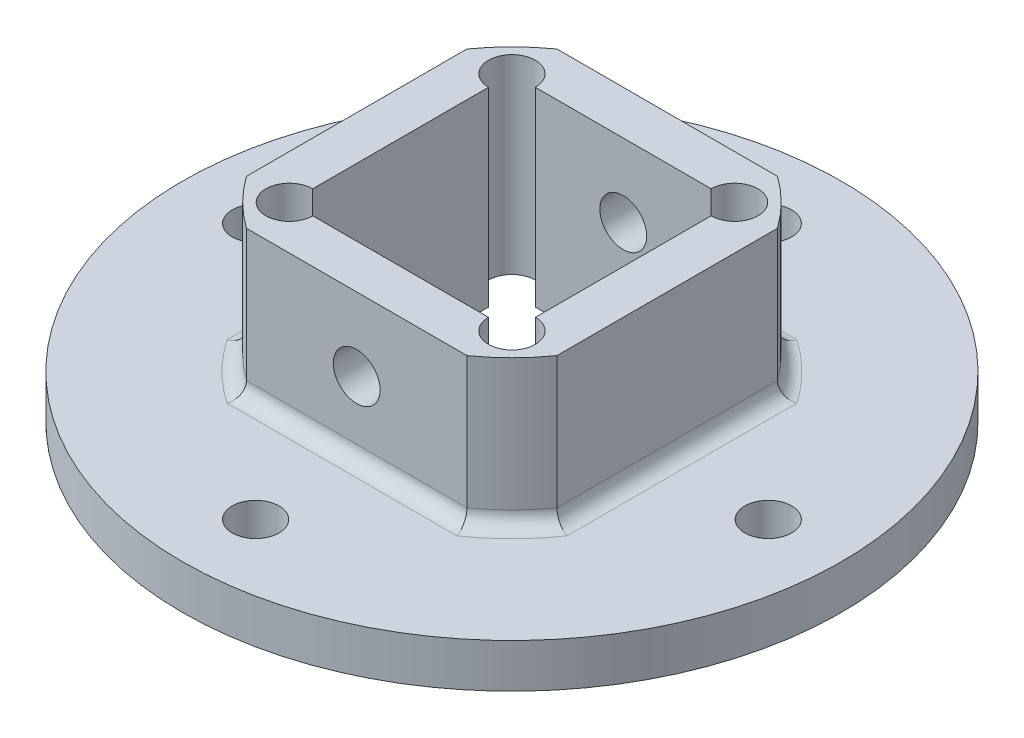
SolidWorks part; units mm, degrees
material "ABS"
ref_plane "前视基准面" through (0, 0, 0) normal (0, 0, 1) x (1, 0, 0)
ref_plane "上视基准面" through (0, 0, 0) normal (0, 1, 0) x (1, 0, 0)
ref_plane "右视基准面" through (0, 0, 0) normal (1, 0, 0) x (0, 0, -1)
other "Configuration Table"
sketch "草图1" plane through (0, 0, 0) normal (0, 1, 0) x (1, 0, 0)
  line L1 (-7.6, -7.6) -> (7.6, -7.6)
  line L2 (-7.6, -7.6) -> (-7.6, 7.6)
  line L3 (-7.6, 7.6) -> (7.6, 7.6)
  line L4 (7.6, -7.6) -> (7.6, 7.6)
  line L5 (-7.6, -7.6) -> (7.6, 7.6) construction
  line L6 (-7.6, 7.6) -> (7.6, -7.6) construction
  circle A0 centre (0, 0) radius 22.5
  circle A1 centre (0, 0) radius 17.5 construction
  circle A2 centre (0, 17.5) radius 1.6
  circle A3 centre (17.5, 0) radius 1.6
  circle A4 centre (0, 0) radius 17.5 construction
  circle A5 centre (0, -17.5) radius 1.6
  circle A6 centre (0, 0) radius 17.5 construction
  circle A7 centre (-17.5, 0) radius 1.6
  circle A8 centre (0, 0) radius 17.5 construction
  point P18 (0, 0)
  dimension "D1" = 45
  dimension "D2" = 35
  dimension "D3" = 1.6
  dimension "D5" = 15.2
  dimension "D4" = 4
extrude "凸台-拉伸1" add sketch "草图1" along normal blind 3
sketch "草图2" plane through (0, 3, 0) normal (0, 1, 0) x (1, 0, 0)
  line L1 (-10.6, -7.526) -> (-10.6, 7.526)
  line L2 (-7.6, -7.6) -> (7.6, -7.6)
  line L3 (-7.6, -7.6) -> (-7.6, 7.6)
  line L4 (-7.6, 7.6) -> (7.6, 7.6)
  line L5 (7.6, -7.6) -> (7.6, 7.6)
  line L6 (-7.6, -7.6) -> (7.6, 7.6) construction
  line L7 (-7.6, 7.6) -> (7.6, -7.6) construction
  line L8 (-7.526, 10.6) -> (7.526, 10.6)
  line L9 (10.6, -7.526) -> (10.6, 7.526)
  line L10 (-7.526, -10.6) -> (7.526, -10.6)
  line L11 (-10.6, 10.6) -> (10.6, 10.6) construction
  line L12 (10.6, -10.6) -> (10.6, 10.6) construction
  line L13 (-10.6, -10.6) -> (10.6, -10.6) construction
  line L14 (-10.6, -10.6) -> (-10.6, 10.6) construction
  arc A0 (10.6, 7.526) -> (7.526, 10.6) centre (0, 0) ccw
  arc A1 (7.526, -10.6) -> (10.6, -7.526) centre (0, 0) ccw
  arc A2 (-10.6, -7.526) -> (-7.526, -10.6) centre (0, 0) ccw
  arc A3 (-7.526, 10.6) -> (-10.6, 7.526) centre (0, 0) ccw
  point P2 (0, 0)
  dimension "D3" = 26
  dimension "D1" = 15.2
  dimension "D2" = 3
extrude "凸台-拉伸2" add sketch "草图2" along normal blind 10
sketch "草图3" plane through (0, 0, -10.6) normal (0, 0, -1) x (-1, 0, 0)
  line L0 (0, 13) -> (0, 0) construction
  line L1 (-7.526, 13) -> (7.526, 13) construction
  circle A0 centre (0, 8) radius 1.6
  dimension "D1" = 3.2
  dimension "D2" = 5
fillet "圆角1" radius 1 8 edges at (-9.1924, 3, 9.1924) (9.1924, 3, 9.1924) (0, 3, 10.6) (10.6, 3, 0) (9.1924, 3, -9.1924) (-9.1924, 3, -9.1924) (0, 3, -10.6) (-10.6, 3, 0)
sketch "草图4" plane through (0, 13, 0) normal (0, 1, 0) x (1, 0, 0)
  circle A0 centre (7.6, 7.6) radius 1.6
  circle A1 centre (7.6, -7.6) radius 1.6
  circle A2 centre (-7.6, -7.6) radius 1.6
  circle A3 centre (-7.6, 7.6) radius 1.6
  dimension "D1" = 3.2
  dimension "D2" = 3.2
  dimension "D3" = 3.2
  dimension "D4" = 3.2
extrude "切除-拉伸2" cut sketch "草图4" against normal through all
extrude "切除-拉伸4" cut sketch "草图3" against normal through all
